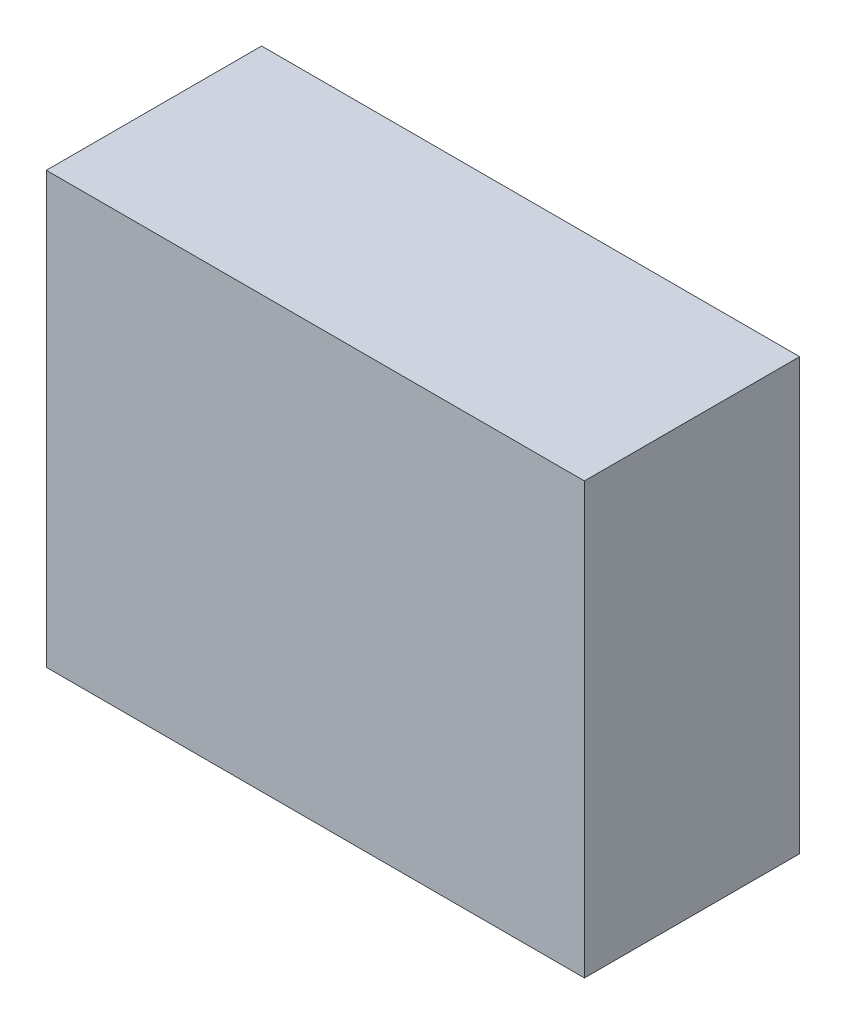
SolidWorks part; units mm, degrees
ref_plane "前视基准面" through (0, 0, 0) normal (0, 0, 1) x (1, 0, 0)
ref_plane "上视基准面" through (0, 0, 0) normal (0, 1, 0) x (1, 0, 0)
ref_plane "右视基准面" through (0, 0, 0) normal (1, 0, 0) x (0, 0, -1)
other "Configuration Table"
sketch "草图1" plane through (0, 0, 0) normal (0, 0, 1) x (1, 0, 0)
  line L1 (0, 0) -> (25, 0)
  line L2 (0, 0) -> (0, 20)
  line L3 (0, 20) -> (25, 20)
  line L4 (25, 0) -> (25, 20)
extrude "凸台-拉伸1" add sketch "草图1" along normal blind 10
